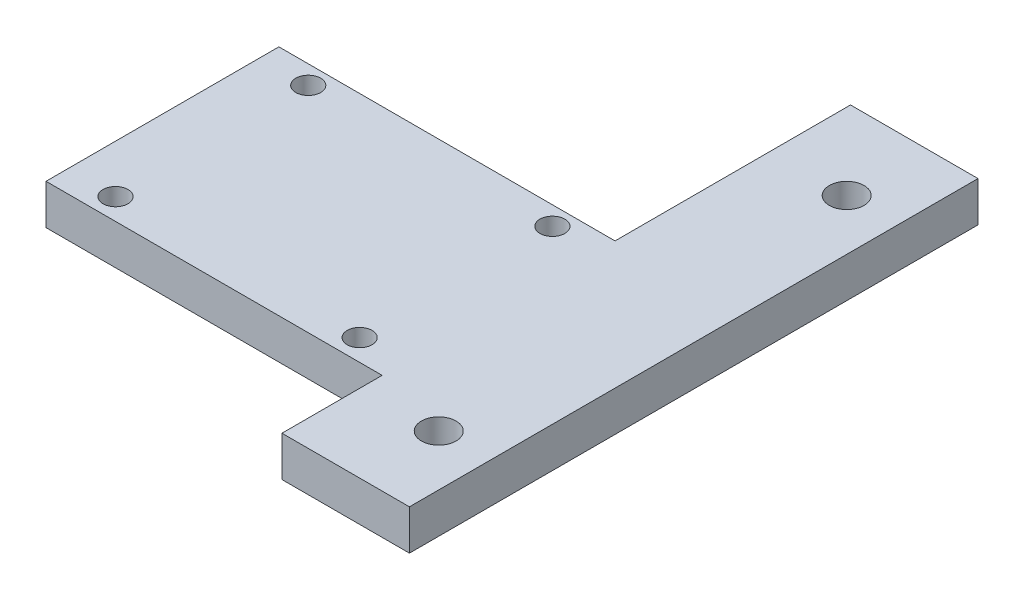
SolidWorks part; units mm, degrees
material "ABS"
ref_plane "Front Plane" through (0, 0, 0) normal (0, 0, 1) x (1, 0, 0)
ref_plane "Top Plane" through (0, 0, 0) normal (0, 1, 0) x (1, 0, 0)
ref_plane "Right Plane" through (0, 0, 0) normal (1, 0, 0) x (0, 0, -1)
sketch "Sketch1" plane through (0, 0, 0) normal (0, 1, 0) x (1, 0, 0)
  line L9 (6.0628, -8.2508) -> (36.55, -8.2508) construction
  line L16 (36.55, 27.1492) -> (36.55, -43.6508)
  line L17 (20.675, -43.6508) -> (36.55, -43.6508)
  line L18 (20.675, -31.174) -> (20.675, -43.6508)
  line L19 (20.675, -31.174) -> (-21.1827, -31.174)
  line L20 (-21.1827, -31.174) -> (-21.1827, -2.174)
  line L21 (-21.1827, -31.174) -> (20.675, -2.174) construction
  line L22 (-21.1827, -2.174) -> (20.675, -31.174) construction
  line L23 (-21.1827, -2.174) -> (20.675, -2.174)
  line L24 (6.0628, 14.5) -> (6.0628, -31.0016) construction
  line L25 (20.675, 27.1492) -> (36.55, 27.1492)
  line L26 (20.675, -2.174) -> (20.675, 27.1492)
  circle A6 centre (30.2, -33.6508) radius 2.159
  circle A7 centre (-15.2, -28.5016) radius 1.55
  circle A8 centre (15.2, -28.5016) radius 1.55
  circle A9 centre (-15.2, -4.5016) radius 1.55
  circle A10 centre (15.2, -4.5016) radius 1.55
  circle A11 centre (30.2, 17.1492) radius 2.159
  dimension "D3" = 4.318
  dimension "D4" = 10
  dimension "D5" = 15.875
  dimension "D9" = 50.8
  dimension "D2" = 4.318
  dimension "D1" = 10
  dimension "D6" = 15.875
  dimension "D7" = 41.8577
  dimension "D8" = 30.4
extrude "Boss-Extrude1" add sketch "Sketch1" along normal blind 5
